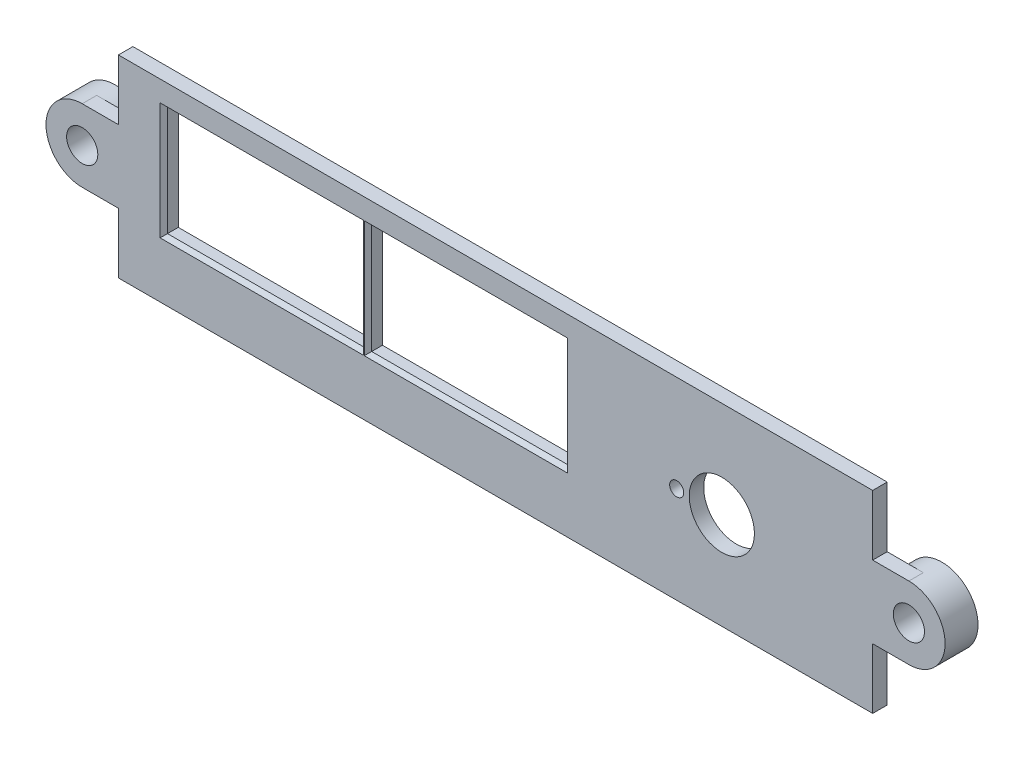
SolidWorks part; units mm, degrees
ref_plane "Front Plane" through (0, 0, 0) normal (0, 0, 1) x (1, 0, 0)
ref_plane "Top Plane" through (0, 0, 0) normal (0, 1, 0) x (1, 0, 0)
ref_plane "Right Plane" through (0, 0, 0) normal (1, 0, 0) x (0, 0, -1)
sketch "Sketch1" plane through (0, 0, 0) normal (0, 0, 1) x (1, 0, 0)
  line L0 (-52.07, 5) -> (-57.07, 5)
  line L1 (-52.07, -13.335) -> (52.07, -13.335)
  line L2 (-52.07, -13.335) -> (-52.07, -5)
  line L3 (-52.07, 13.335) -> (52.07, 13.335)
  line L5 (-57.07, -5) -> (-52.07, -5)
  line L6 (-52.07, 5) -> (-52.07, 13.335)
  line L7 (0, 13.335) -> (0, -13.335) construction
  line L8 (52.07, 5) -> (52.07, 13.335)
  line L9 (57.07, -5) -> (52.07, -5)
  line L10 (52.07, -13.335) -> (52.07, -5)
  line L11 (52.07, 5) -> (57.07, 5)
  arc A0 (-57.07, 5) -> (-57.07, -5) centre (-57.07, 0) ccw
  arc A1 (57.07, 5) -> (57.07, -5) centre (57.07, 0) cw
  point P1 (0, 0)
  dimension "D4" = 5
  dimension "D1" = 26.67
  dimension "D2" = 52.07
  dimension "D3" = 5
extrude "Boss-Extrude1" add sketch "Sketch1" along normal blind 2
sketch "Sketch5" plane through (0, 0, 0) normal (0, 0, 1) x (1, 0, 0)
  circle A0 centre (-57.07, 0) radius 5
  circle A1 centre (57.07, 0) radius 5
  arc A4 (57.07, -5) -> (57.07, 5) centre (57.07, 0) ccw construction
  point P7 (54.9074, 1.168)
  point P10 (0, 0)
extrude "Boss-Extrude2" add sketch "Sketch5" against normal blind 2.54
sketch "Sketch6" plane through (0, 0, -2.54) normal (0, 0, -1) x (-1, 0, 0)
  point P0 (57.07, 0)
  point P1 (-57.07, 0)
hole_wizard "#18 (0.1695) Diameter Hole1" positions "Sketch6" profile "Sketch7" hole size "#18" standard "ANSI Inch"
sketch "Sketch7" plane through (-57.07, 0, -2.54) normal (1, 0, 0) x (0, 1, 0)
  line L0 (0, 0) -> (0, 5.8654)
  line L1 (0, 5.8654) -> (2.1526, 4.572)
  line L2 (2.1526, 4.572) -> (2.1526, 0.3874)
  line L3 (2.1526, 0.3874) -> (2.54, 0)
  line L5 (2.54, 0) -> (0, 0)
  line L6 (-2.1526, 0.3874) -> (-2.54, 0) construction
  line L10 (0, 5.8654) -> (-2.1526, 4.572) construction
  line L11 (0, -6.35) -> (0, 107.95) construction
  dimension "Hole Dia." = 4.3053
  dimension "Hole Depth" = 4.572
  dimension "Near C'Sink Dia." = 5.08
  dimension "Near C'Sink Angle" = 90
  dimension "Drill Angle" = 118
sketch "Sketch2" plane through (0, 0, 2) normal (0, 0, 1) x (1, 0, 0)
  line L0 (52.07, 5) -> (52.07, -4.9778) construction
  line L5 (-46.24, 13.97) -> (-18.3, 13.97) construction
  line L6 (-46.24, 13.97) -> (-46.24, -13.97) construction
  line L7 (-46.24, -13.97) -> (-18.3, -13.97) construction
  line L8 (-18.3, 13.97) -> (-18.3, -13.97) construction
  line L9 (-18.05, 13.97) -> (9.89, 13.97) construction
  line L10 (-18.05, 13.97) -> (-18.05, -13.97) construction
  line L11 (-18.05, -13.97) -> (9.89, -13.97) construction
  line L12 (9.89, 13.97) -> (9.89, -13.97) construction
  line L13 (-17.415, 9.779) -> (9.255, 9.779) construction
  line L14 (-45.605, 9.779) -> (-18.935, 9.779) construction
  line L15 (-45.605, 9.779) -> (-45.605, -4.953) construction
  line L16 (-45.605, -4.953) -> (-18.935, -4.953) construction
  line L17 (-18.935, 9.779) -> (-18.935, -4.953) construction
  line L18 (-17.415, 9.779) -> (-17.415, -4.953) construction
  line L19 (-17.415, -4.953) -> (9.255, -4.953) construction
  line L20 (9.255, 9.779) -> (9.255, -4.953) construction
  line L21 (52.07, 0.0111) -> (46.24, 0) construction
  line L22 (9.89, 0) -> (16.24, 0) construction
  line L23 (-46.24, 0) -> (-52.07, 0) construction
  circle A0 centre (31.24, 0) radius 15 construction
  circle A1 centre (31.24, 0) radius 4.5 construction
  arc A2 (-57.07, 5) -> (-57.07, -5) centre (-57.07, 0) ccw construction
  point P17 (-32.27, 13.97)
  point P18 (-32.27, 9.779)
  point P24 (-4.08, 13.97)
  point P27 (-4.08, 9.779)
  dimension "D7" = 30
  dimension "D9" = 9
  dimension "D8" = 6.35
  dimension "D1" = 27.94
  dimension "D2" = 0.25
  dimension "D3" = 4.191
  dimension "D4" = 26.67
  dimension "D5" = 14.732
  dimension "D6" = 26.67
sketch "Sketch3" plane through (0, 0, 2) normal (0, 0, 1) x (1, 0, 0)
  line L0 (-17.615, 9.779) -> (-17.415, 9.779) construction
  line L9 (-17.615, 9.979) -> (9.455, 9.979)
  line L10 (-17.615, 9.979) -> (-17.615, -5.153)
  line L11 (-17.615, -5.153) -> (9.455, -5.153)
  line L12 (9.455, 9.979) -> (9.455, -5.153)
  line L13 (-17.415, 9.779) -> (-17.415, 9.979) construction
  line L14 (9.455, -4.953) -> (9.255, -4.953) construction
  line L15 (9.255, -4.953) -> (9.255, -5.153) construction
  line L16 (-45.805, -4.953) -> (-45.605, -4.953) construction
  line L17 (-18.735, 9.979) -> (-45.805, 9.979)
  line L18 (-18.735, 9.979) -> (-18.735, -5.153)
  line L19 (-18.735, -5.153) -> (-45.805, -5.153)
  line L20 (-45.805, 9.979) -> (-45.805, -5.153)
  line L21 (-45.605, -4.953) -> (-45.605, -5.153) construction
  line L22 (-18.935, 9.979) -> (-18.935, 9.779) construction
  line L23 (-18.935, 9.779) -> (-18.735, 9.779) construction
  line L24 (25.0108, 0) -> (26.74, 0) construction
  circle A0 centre (31.24, 0) radius 4.5
  circle A1 centre (25.0108, 0) radius 0.9724
  dimension "D2" = 9
  dimension "D1" = 0.2
extrude "Cut-Extrude1" cut sketch "Sketch3" against normal through all
chamfer "Chamfer1" distance 0.508 angle 45 8 edges at (-4.08, -5.153, 2) (9.455, 2.413, 2) (-4.08, 9.979, 2) (-17.615, 2.413, 2) (-18.735, 2.413, 2) (-32.27, 9.979, 2) (-45.805, 2.413, 2) (-32.27, -5.153, 2)
